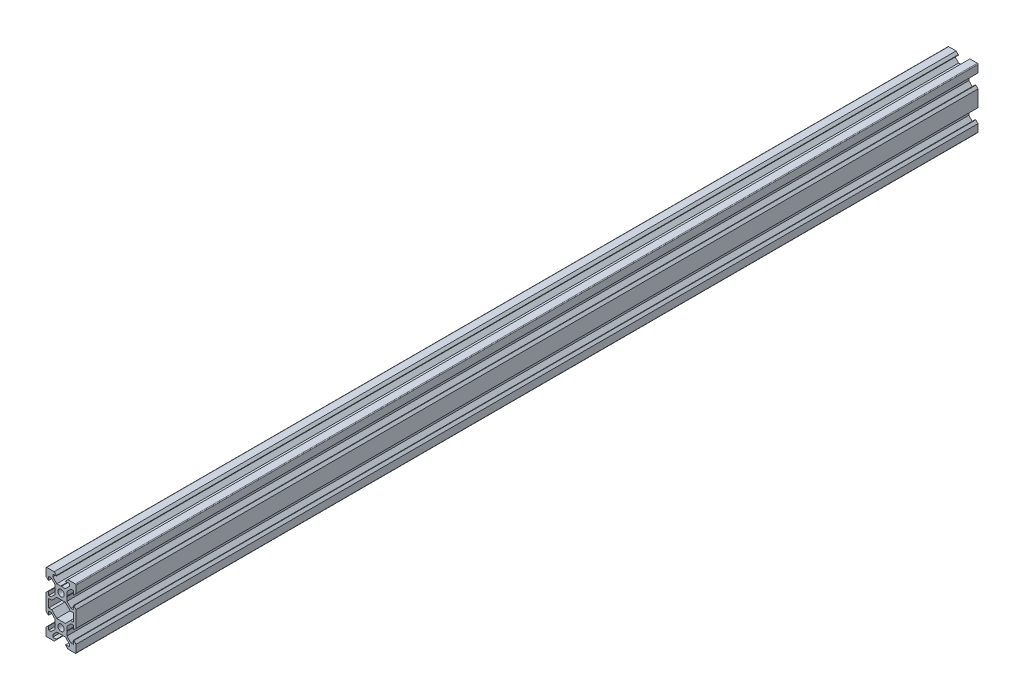
SolidWorks part; units mm, degrees
material "6061-T6 (SS)"
ref_plane "Front Plane" through (0, 0, 0) normal (0, 0, 1) x (1, 0, 0)
ref_plane "Top Plane" through (0, 0, 0) normal (0, 1, 0) x (1, 0, 0)
ref_plane "Right Plane" through (0, 0, 0) normal (1, 0, 0) x (0, 0, -1)
sketch "Sketch1" plane through (0, 0, 0) normal (0, 0, 1) x (1, 0, 0)
  line L0 (0, 0) -> (10, 0) construction
  line L1 (9.5, -20) -> (-9.5, -20)
  line L2 (10, -19.5) -> (10, 19.5)
  line L3 (9.5, 20) -> (-9.5, 20)
  line L4 (-10, -19.5) -> (-10, 19.5)
  line L5 (10, -20) -> (-10, 20) construction
  line L6 (10, 20) -> (-10, -20) construction
  circle A0 centre (0, 10) radius 2.1
  circle A1 centre (0, -10) radius 2.1
  arc A2 (-9.5, -20) -> (-10, -19.5) centre (-9.5, -19.5) cw
  arc A3 (9.5, -20) -> (10, -19.5) centre (9.5, -19.5) ccw
  arc A4 (10, 19.5) -> (9.5, 20) centre (9.5, 19.5) ccw
  arc A5 (-9.5, 20) -> (-10, 19.5) centre (-9.5, 19.5) ccw
  point P0 (0, 0)
  line B0 (0, 10) -> (0, 20) construction
  line B1 (0, 13.69) -> (-0.21, 13.9)
  line B2 (-0.21, 13.9) -> (-2.8393, 13.9)
  line B3 (-2.8393, 13.9) -> (-5.5, 16.5607)
  line B4 (-5.5, 16.5607) -> (-5.5, 18.2)
  line B5 (-5.5, 18.2) -> (-3.125, 18.2)
  line B6 (-3.125, 18.2) -> (-3.125, 18.545)
  line B7 (-3.125, 18.545) -> (-4.58, 20)
  line B8 (-4.58, 20) -> (4.58, 20)
  line B9 (0, 10) -> (-5.9132, 15.9132) construction
  line B10 (3.125, 18.545) -> (4.58, 20)
  line B11 (3.125, 18.2) -> (3.125, 18.545)
  line B12 (5.5, 18.2) -> (3.125, 18.2)
  line B13 (5.5, 16.5607) -> (5.5, 18.2)
  line B14 (2.8393, 13.9) -> (5.5, 16.5607)
  line B15 (0.21, 13.9) -> (2.8393, 13.9)
  line B16 (0, 13.69) -> (0.21, 13.9)
  line B17 (0, 10) -> (-10, 10) construction
  line B18 (-3.69, 10) -> (-3.9, 9.79)
  line B19 (-3.9, 9.79) -> (-3.9, 7.1607)
  line B20 (-3.9, 7.1607) -> (-6.5607, 4.5)
  line B21 (-6.5607, 4.5) -> (-8.2, 4.5)
  line B22 (-8.2, 4.5) -> (-8.2, 6.875)
  line B23 (-8.2, 6.875) -> (-8.545, 6.875)
  line B24 (-8.545, 6.875) -> (-10, 5.42)
  line B25 (-10, 5.42) -> (-10, 14.58)
  line B26 (0, 10) -> (-5.9132, 4.0868) construction
  line B27 (-8.545, 13.125) -> (-10, 14.58)
  line B28 (-8.2, 13.125) -> (-8.545, 13.125)
  line B29 (-8.2, 15.5) -> (-8.2, 13.125)
  line B30 (-6.5607, 15.5) -> (-8.2, 15.5)
  line B31 (-3.9, 12.8393) -> (-6.5607, 15.5)
  line B32 (-3.9, 10.21) -> (-3.9, 12.8393)
  line B33 (-3.69, 10) -> (-3.9, 10.21)
  line B34 (0, -10) -> (-10, -10) construction
  line B35 (-3.69, -10) -> (-3.9, -10.21)
  line B36 (-3.9, -10.21) -> (-3.9, -12.8393)
  line B37 (-3.9, -12.8393) -> (-6.5607, -15.5)
  line B38 (-6.5607, -15.5) -> (-8.2, -15.5)
  line B39 (-8.2, -15.5) -> (-8.2, -13.125)
  line B40 (-8.2, -13.125) -> (-8.545, -13.125)
  line B41 (-8.545, -13.125) -> (-10, -14.58)
  line B42 (-10, -14.58) -> (-10, -5.42)
  line B43 (0, -10) -> (-5.9132, -15.9132) construction
  line B44 (-8.545, -6.875) -> (-10, -5.42)
  line B45 (-8.2, -6.875) -> (-8.545, -6.875)
  line B46 (-8.2, -4.5) -> (-8.2, -6.875)
  line B47 (-6.5607, -4.5) -> (-8.2, -4.5)
  line B48 (-3.9, -7.1607) -> (-6.5607, -4.5)
  line B49 (-3.9, -9.79) -> (-3.9, -7.1607)
  line B50 (-3.69, -10) -> (-3.9, -9.79)
  line B51 (0, -10) -> (0, -20) construction
  line B52 (0, -13.69) -> (0.21, -13.9)
  line B53 (0.21, -13.9) -> (2.8393, -13.9)
  line B54 (2.8393, -13.9) -> (5.5, -16.5607)
  line B55 (5.5, -16.5607) -> (5.5, -18.2)
  line B56 (5.5, -18.2) -> (3.125, -18.2)
  line B57 (3.125, -18.2) -> (3.125, -18.545)
  line B58 (3.125, -18.545) -> (4.58, -20)
  line B59 (4.58, -20) -> (-4.58, -20)
  line B60 (0, -10) -> (5.9132, -15.9132) construction
  line B61 (-3.125, -18.545) -> (-4.58, -20)
  line B62 (-3.125, -18.2) -> (-3.125, -18.545)
  line B63 (-5.5, -18.2) -> (-3.125, -18.2)
  line B64 (-5.5, -16.5607) -> (-5.5, -18.2)
  line B65 (-2.8393, -13.9) -> (-5.5, -16.5607)
  line B66 (-0.21, -13.9) -> (-2.8393, -13.9)
  line B67 (0, -13.69) -> (-0.21, -13.9)
  line B68 (0, -10) -> (10, -10) construction
  line B69 (3.69, -10) -> (3.9, -9.79)
  line B70 (3.9, -9.79) -> (3.9, -7.1607)
  line B71 (3.9, -7.1607) -> (6.5607, -4.5)
  line B72 (6.5607, -4.5) -> (8.2, -4.5)
  line B73 (8.2, -4.5) -> (8.2, -6.875)
  line B74 (8.2, -6.875) -> (8.545, -6.875)
  line B75 (8.545, -6.875) -> (10, -5.42)
  line B76 (10, -5.42) -> (10, -14.58)
  line B77 (0, -10) -> (5.9132, -4.0868) construction
  line B78 (8.545, -13.125) -> (10, -14.58)
  line B79 (8.2, -13.125) -> (8.545, -13.125)
  line B80 (8.2, -15.5) -> (8.2, -13.125)
  line B81 (6.5607, -15.5) -> (8.2, -15.5)
  line B82 (3.9, -12.8393) -> (6.5607, -15.5)
  line B83 (3.9, -10.21) -> (3.9, -12.8393)
  line B84 (3.69, -10) -> (3.9, -10.21)
  line B85 (0, 10) -> (10, 10) construction
  line B86 (3.69, 10) -> (3.9, 10.21)
  line B87 (3.9, 10.21) -> (3.9, 12.8393)
  line B88 (3.9, 12.8393) -> (6.5607, 15.5)
  line B89 (6.5607, 15.5) -> (8.2, 15.5)
  line B90 (8.2, 15.5) -> (8.2, 13.125)
  line B91 (8.2, 13.125) -> (8.545, 13.125)
  line B92 (8.545, 13.125) -> (10, 14.58)
  line B93 (10, 14.58) -> (10, 5.42)
  line B94 (0, 10) -> (5.9132, 15.9132) construction
  line B95 (8.545, 6.875) -> (10, 5.42)
  line B96 (8.2, 6.875) -> (8.545, 6.875)
  line B97 (8.2, 4.5) -> (8.2, 6.875)
  line B98 (6.5607, 4.5) -> (8.2, 4.5)
  line B99 (3.9, 7.1607) -> (6.5607, 4.5)
  line B100 (3.9, 9.79) -> (3.9, 7.1607)
  line B101 (3.69, 10) -> (3.9, 9.79)
  line B102 (-8.2, -2.7) -> (-8.2, 2.7)
  line B103 (-8.2, 2.7) -> (-6.2393, 2.7)
  line B104 (-6.2393, 2.7) -> (-2.8393, 6.1)
  line B105 (-2.8393, 6.1) -> (2.8393, 6.1)
  line B106 (0, 6.1) -> (0, 0) construction
  line B107 (0, 0) -> (-8.2, 0) construction
  line B108 (6.2393, 2.7) -> (2.8393, 6.1)
  line B109 (8.2, 2.7) -> (6.2393, 2.7)
  line B110 (8.2, -2.7) -> (8.2, 2.7)
  line B111 (8.2, -2.7) -> (6.2393, -2.7)
  line B112 (6.2393, -2.7) -> (2.8393, -6.1)
  line B113 (-2.8393, -6.1) -> (2.8393, -6.1)
  line B114 (-6.2393, -2.7) -> (-2.8393, -6.1)
  line B115 (-8.2, -2.7) -> (-6.2393, -2.7)
  line B116 (0, 6.1) -> (0, 10) construction
  line B117 (0, 10) -> (-5.0927, 4.9073) construction
  dimension "D4" = 4.2
  dimension "D5" = 0.5
  dimension "D1" = 20
  dimension "D2" = 40
  dimension "D3" = 20
sketch_block_instance "V Slot 1-4"
sketch_block "V Slot 1" parameters "D1"=10, "D2"=11, "D3"=4.3, "D4"=1.8, "D5"=0.21, "D6"=45, "D7"=9.16, "D8"=1.5, "D9"=6.25
sketch_block_instance "V Slot 1-5"
sketch_block_instance "V Slot 1-6"
sketch_block_instance "V Slot 1-7"
sketch_block_instance "V Slot 1-8"
sketch_block_instance "V Slot 1-9"
sketch_block_instance "Center Cutout 1-1"
sketch_block "Center Cutout 1" parameters "D1"=5.4, "D2"=12.2, "D3"=8.2, "D4"=45, "D5"=10, "D6"=1.5
extrude "Boss-Extrude1" add sketch "Sketch1" along normal blind 600 contours B101 B86 B87 B88 B89 B90 B91 B92 L2 A4 L3 B10 B11 B12 B13 B14 B15 B16 B1 B2 B3 B4 B5 B6 B7 A5 L4 B27 B28 B29 B30 B31 B32 B33 B18 B19 B20 B21 B22 B23 B24 B44 B45 B46 B47 B48 B49 B50 B35
